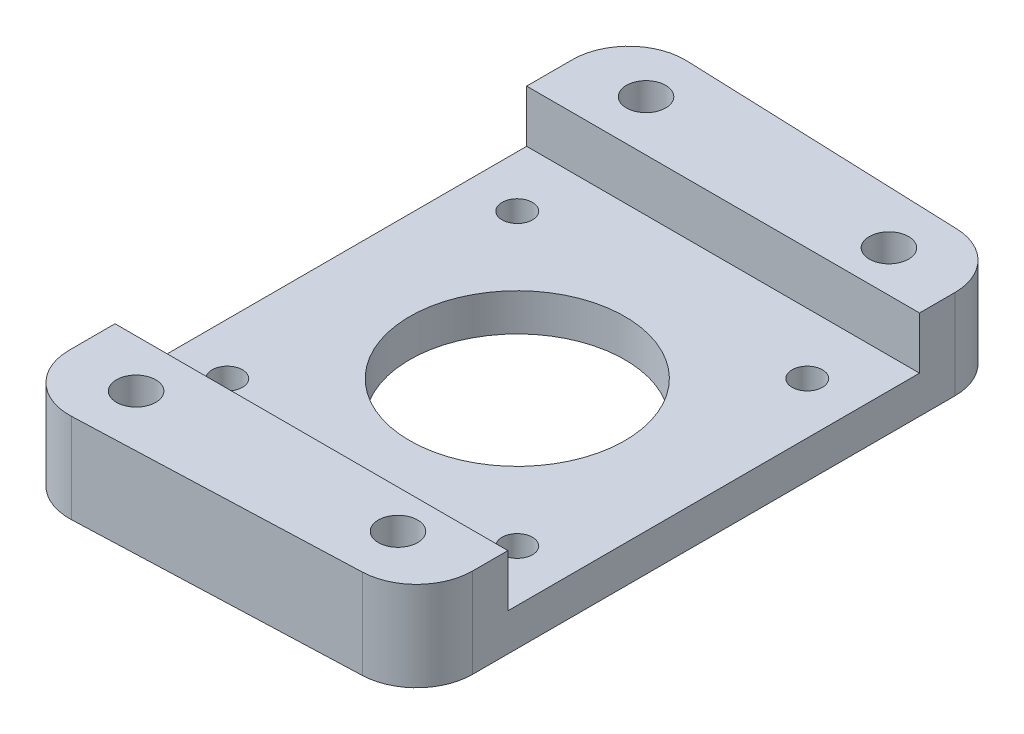
SolidWorks part; units mm, degrees
ref_plane "Front Plane" through (0, 0, 0) normal (0, 0, 1) x (1, 0, 0)
ref_plane "Top Plane" through (0, 0, 0) normal (0, 1, 0) x (1, 0, 0)
ref_plane "Right Plane" through (0, 0, 0) normal (1, 0, 0) x (0, 0, -1)
sketch "Sketch1" plane through (0, 0, 0) normal (0, 1, 0) x (1, 0, 0)
  line L12 (21, 31.7021) -> (21, -31.4021) construction
  line L13 (-21, -33.1323) -> (21, -31.5521)
  line L14 (-21, -33.1323) -> (-21, 33.1323)
  line L15 (-21, 33.1323) -> (21, 31.5521)
  line L16 (21, -31.5521) -> (21, 31.5521)
  line L17 (128.7, 27.65) -> (-69.9841, 35.1253) construction
  line L18 (128.7, -27.35) -> (-69.9841, -34.8253) construction
  line L19 (-21, -32.9823) -> (-21, 33.2823) construction
  point P4 (0, 0)
  point P6 (0, -32.3422)
  point P7 (21, 0)
  dimension "D3" = 42
extrude "Boss-Extrude1" add sketch "Sketch1" along normal blind 4
sketch "Sketch3" plane through (0, 4, 0) normal (0, 1, 0) x (1, 0, 0)
  circle A0 centre (0, 0) radius 11.5
  dimension "22.4" = 23
extrude "Cut-Extrude1" cut sketch "Sketch3" against normal through all
sketch "Sketch4" plane through (0, 4, 0) normal (0, 1, 0) x (1, 0, 0)
  line L0 (-15.5, 15.5) -> (15.5, 15.5) construction
  line L1 (15.5, 15.5) -> (15.5, -15.5) construction
  line L2 (15.5, -15.5) -> (-15.5, -15.5) construction
  line L3 (-15.5, -15.5) -> (-15.5, 15.5) construction
  circle A0 centre (-15.5, 15.5) radius 1.625
  circle A1 centre (15.5, 15.5) radius 1.625
  circle A2 centre (15.5, -15.5) radius 1.625
  circle A3 centre (-15.5, -15.5) radius 1.625
  point P8 (15.5, 0)
  point P9 (0, 15.5)
  dimension "D2" = 3.25
  dimension "D1" = 31
extrude "Cut-Extrude2" cut sketch "Sketch4" against normal through all
sketch "Sketch6" plane through (0, 4, 0) normal (0, -1, 0) x (1, 0, 0)
  line L4 (21, 22) -> (-21, 22)
  line L8 (-21, 22) -> (-21, 33.1323)
  line L9 (-21, 33.1323) -> (21, 31.5521)
  line L10 (21, 31.5521) -> (21, 22)
  line L11 (21, 31.5521) -> (21, -31.5521) construction
  point P4 (19.8456, 31.2312)
  dimension "D1" = 22
extrude "Boss-Extrude2" add sketch "Sketch6" against normal blind 5.575
mirror "Mirror1" about plane through (0, 0, 0) normal (0, 0, 1) of "Boss-Extrude2"
sketch "Sketch7" plane through (0, 9.575, 0) normal (0, 1, 0) x (1, 0, 0)
  circle A0 centre (-13.6405, -27.1065) radius 2.1
  circle A1 centre (13.3405, -26.0914) radius 2.1
  circle A2 centre (13.3405, 26.3914) radius 2.1
  circle A3 centre (-13.6405, 27.4065) radius 2.1
  dimension "D1" = 4.2
extrude "Cut-Extrude3" cut sketch "Sketch7" against normal blind 6
fillet "Fillet1" radius 6 4 edges at (-21, 4.7875, -33.1323) (21, 4.7875, -31.5521) (21, 4.7875, 31.5521) (-21, 4.7875, 33.1323)
